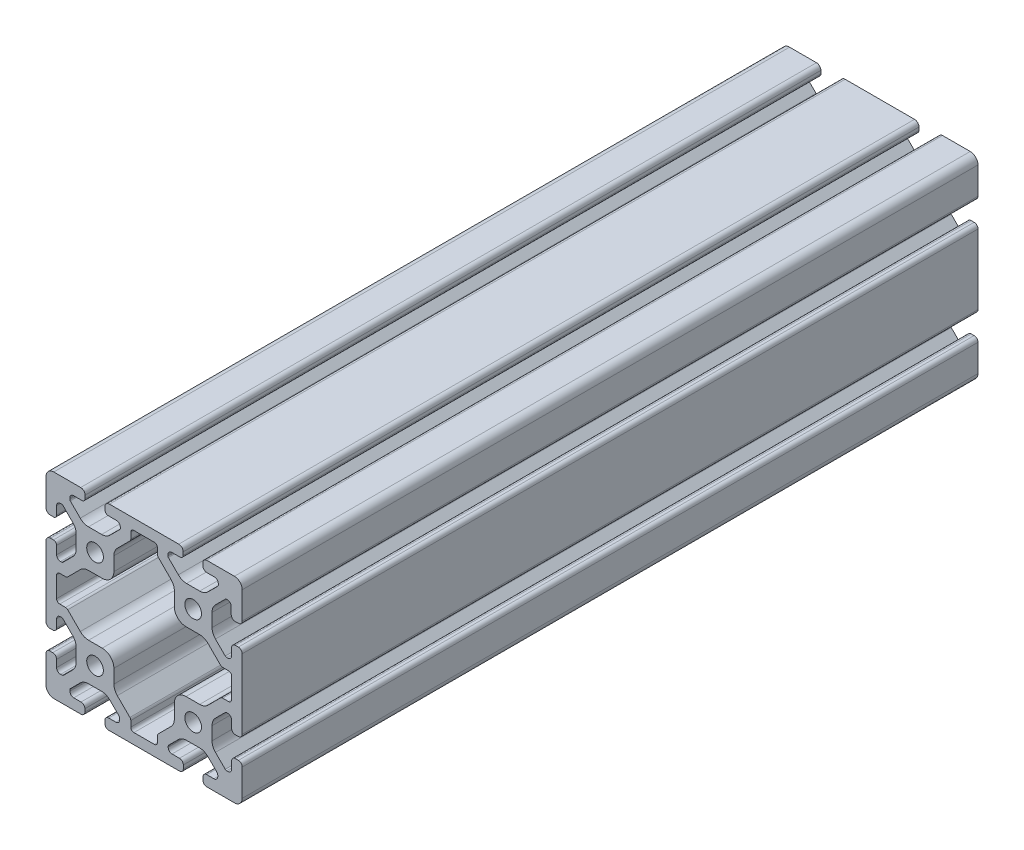
SolidWorks part; units mm, degrees
material "6105-T5 Aluminum"
ref_plane "Front Plane" through (0, 0, 0) normal (0, 0, 1) x (1, 0, 0)
ref_plane "Top Plane" through (0, 0, 0) normal (0, 1, 0) x (1, 0, 0)
ref_plane "Right Plane" through (0, 0, 0) normal (1, 0, 0) x (0, 0, -1)
sketch "Sketch1" plane through (0, 0, 0) normal (0, 0, 1) x (1, 0, 0)
  line L1 (0, 0) -> (-43.5804, 43.5804) construction
  line L2 (-20, 20) -> (-47.7323, 20) construction
  line L3 (-20, 20) -> (3.796, 43.796) construction
  line L4 (-20, 20) -> (-20, 43.5758) construction
  line L5 (-20, -27.7) -> (-20, -47.5576) construction
  line L131 (29.0912, 26.0365) -> (33.0827, 30.028)
  line L132 (27.7, 17.3222) -> (27.7, 22.6778)
  line L133 (29.0912, 13.9635) -> (33.0827, 9.972)
  line L134 (33.6201, 9.7494) -> (34.11, 9.7494)
  line L135 (35.68, 11.3194) -> (35.68, 14.2221)
  line L136 (37.25, 15.7921) -> (38.43, 15.7921)
  line L137 (40, 14.2221) -> (40, 7.0214)
  line L138 (40, 7.0214) -> (40, -7.0214)
  line L139 (40, -7.0214) -> (40, -14.2221)
  line L140 (38.43, -15.7921) -> (37.25, -15.7921)
  line L141 (35.68, -14.2221) -> (35.68, -11.3194)
  line L142 (33.6201, -9.7494) -> (34.11, -9.7494)
  line L143 (29.0912, -13.9635) -> (33.0827, -9.972)
  line L144 (27.7, -22.6778) -> (27.7, -17.3222)
  line L145 (29.0912, -26.0365) -> (33.0827, -30.028)
  line L146 (33.6201, -30.2506) -> (34.11, -30.2506)
  line L147 (35.68, -28.6806) -> (35.68, -25.7779)
  line L148 (37.25, -24.2079) -> (38.43, -24.2079)
  line L149 (40, -25.7779) -> (40, -33.0259)
  line L150 (40, -33.0259) -> (40, -36.83)
  line L151 (36.83, -40) -> (32.9998, -40)
  line L152 (32.9998, -40) -> (25.5696, -40)
  line L153 (23.9996, -38.43) -> (23.9996, -37.25)
  line L154 (25.5696, -35.68) -> (28.4723, -35.68)
  line L155 (30.0413, -34.0552) -> (30.0171, -33.3605)
  line L156 (29.7949, -32.8496) -> (26.0365, -29.0912)
  line L157 (17.3222, -27.7) -> (22.6778, -27.7)
  line L158 (10.035, -33.0197) -> (13.9635, -29.0912)
  line L159 (9.8124, -33.8926) -> (9.8124, -33.5571)
  line L160 (11.3824, -35.4626) -> (14.4246, -35.4626)
  line L161 (15.9946, -37.0326) -> (15.9946, -38.43)
  line L162 (14.4246, -40) -> (6.9987, -40)
  line L163 (6.9987, -40) -> (-6.9987, -40)
  line L164 (-6.9987, -40) -> (-14.4292, -40)
  line L165 (-15.9992, -38.43) -> (-15.9992, -37.25)
  line L166 (-14.4292, -35.68) -> (-11.5265, -35.68)
  line L167 (-9.9574, -34.0552) -> (-9.9816, -33.3618)
  line L168 (-10.2038, -32.8509) -> (-13.9635, -29.0912)
  line L169 (-22.6778, -27.7) -> (-17.3222, -27.7)
  line L170 (-30.028, -33.0827) -> (-26.0365, -29.0912)
  line L171 (-30.2506, -34.11) -> (-30.2506, -33.6201)
  line L172 (-28.6806, -35.68) -> (-25.7231, -35.68)
  line L173 (-24.1531, -37.25) -> (-24.1531, -38.43)
  line L174 (-25.7231, -40) -> (-33, -40)
  line L175 (-33, -40) -> (-36.83, -40)
  line L176 (-40, -36.83) -> (-40, -33.0191)
  line L177 (-40, -33.0191) -> (-40, -25.591)
  line L178 (-38.43, -24.021) -> (-37.25, -24.021)
  line L179 (-35.68, -28.4937) -> (-35.68, -25.591)
  line L180 (-34.0552, -30.0627) -> (-33.3827, -30.0392)
  line L181 (-32.8718, -29.8171) -> (-29.0912, -26.0365)
  line L182 (-27.7, -22.6778) -> (-27.7, -17.3222)
  line L183 (-29.0912, -13.9635) -> (-33.0827, -9.972)
  line L184 (-34.11, -9.7494) -> (-33.6201, -9.7494)
  line L185 (-35.68, -11.3194) -> (-35.68, -14.4473)
  line L186 (-38.43, -16.0173) -> (-37.25, -16.0173)
  line L187 (-40, -14.4473) -> (-40, -7.0169)
  line L188 (-40, -7.0169) -> (-40, 7.0169)
  line L189 (-40, 7.0169) -> (-40, 14.1348)
  line L190 (-38.1948, 15.94) -> (-36.9772, 15.94)
  line L191 (-35.68, 11.3194) -> (-35.68, 14.6428)
  line L192 (-34.11, 9.7494) -> (-33.6201, 9.7494)
  line L193 (-33.0827, 9.972) -> (-29.0912, 13.9635)
  line L194 (-27.7, 17.3222) -> (-27.7, 22.6778)
  line L195 (-29.0912, 26.0365) -> (-33.0827, 30.028)
  line L196 (-34.11, 30.2506) -> (-33.6201, 30.2506)
  line L197 (-35.68, 28.6806) -> (-35.68, 25.3572)
  line L198 (-38.1948, 24.06) -> (-36.9772, 24.06)
  line L199 (-40, 25.8652) -> (-40, 33.3181)
  line L200 (-40, 33.3181) -> (-40, 36.83)
  line L201 (-36.83, 40) -> (-33.0314, 40)
  line L202 (-33.0314, 40) -> (-25.8652, 40)
  line L203 (-24.06, 36.9772) -> (-24.06, 38.1948)
  line L204 (-25.3572, 35.68) -> (-28.7018, 35.68)
  line L205 (-30.285, 33.6069) -> (-30.285, 34.0968)
  line L206 (-30.0961, 33.1508) -> (-26.0365, 29.0912)
  line L207 (-22.6778, 27.7) -> (-17.3222, 27.7)
  line L208 (-13.9635, 29.0912) -> (-9.9039, 33.1508)
  line L209 (-9.715, 33.6069) -> (-9.715, 34.0968)
  line L210 (-14.6428, 35.68) -> (-11.2982, 35.68)
  line L211 (-15.94, 36.9772) -> (-15.94, 38.1948)
  line L212 (-14.1348, 40) -> (-6.9844, 40)
  line L213 (-6.9844, 40) -> (6.9844, 40)
  line L214 (6.9844, 40) -> (14.1348, 40)
  line L215 (15.94, 36.9772) -> (15.94, 38.1948)
  line L216 (14.6428, 35.68) -> (11.2982, 35.68)
  line L217 (9.715, 33.6069) -> (9.715, 34.0968)
  line L218 (9.9039, 33.1508) -> (13.9635, 29.0912)
  line L219 (17.3222, 27.7) -> (22.6778, 27.7)
  line L220 (26.0365, 29.0912) -> (30.028, 33.0827)
  line L221 (30.2506, 33.6201) -> (30.2506, 34.11)
  line L222 (25.5409, 35.679) -> (28.6258, 35.679)
  line L223 (23.9709, 37.249) -> (23.9709, 38.43)
  line L224 (25.5409, 40) -> (36.83, 40)
  line L226 (40, 36.83) -> (40, 32.9339)
  line L227 (40, 32.9339) -> (40, 25.7779)
  line L228 (38.43, 24.2079) -> (37.0956, 24.2079)
  line L229 (35.5256, 25.7779) -> (35.5256, 28.6806)
  line L230 (33.6201, 30.2506) -> (33.9556, 30.2506)
  line L231 (17.07, 12.32) -> (22.6578, 12.32)
  line L232 (26.0165, 10.9288) -> (31.1439, 5.8014)
  line L233 (32.0419, 5.4294) -> (34.41, 5.4294)
  line L234 (35.68, -4.1594) -> (35.68, 4.1594)
  line L235 (32.0419, -5.4294) -> (34.41, -5.4294)
  line L236 (26.0165, -10.9288) -> (31.1439, -5.8014)
  line L237 (17.07, -12.32) -> (22.6578, -12.32)
  line L238 (12.32, -22.6578) -> (12.32, -17.07)
  line L239 (5.8014, -31.1439) -> (10.9288, -26.0165)
  line L240 (5.4294, -34.41) -> (5.4294, -32.0419)
  line L241 (-4.1594, -35.68) -> (4.1594, -35.68)
  line L242 (-5.4294, -34.41) -> (-5.4294, -32.0419)
  line L243 (-5.8014, -31.1439) -> (-10.9288, -26.0165)
  line L244 (-12.32, -22.6578) -> (-12.32, -17.07)
  line L245 (-22.6578, -12.32) -> (-17.07, -12.32)
  line L246 (-26.0165, -10.9288) -> (-31.1439, -5.8014)
  line L247 (-34.41, -5.4294) -> (-32.0419, -5.4294)
  line L248 (-35.68, -4.1594) -> (-35.68, 4.1594)
  line L249 (-34.41, 5.4294) -> (-32.0419, 5.4294)
  line L250 (-31.1439, 5.8014) -> (-26.0165, 10.9288)
  line L251 (-22.6578, 12.32) -> (-17.07, 12.32)
  line L252 (-12.32, 17.07) -> (-12.32, 22.6578)
  line L253 (-10.9288, 26.0165) -> (-5.8014, 31.1439)
  line L254 (-5.4294, 32.0419) -> (-5.4294, 34.41)
  line L255 (-4.1594, 35.68) -> (4.1594, 35.68)
  line L256 (5.4294, 32.0419) -> (5.4294, 34.41)
  line L257 (5.8014, 31.1439) -> (10.9288, 26.0165)
  line L258 (12.32, 17.07) -> (12.32, 22.6578)
  circle A116 centre (-20, 20) radius 3.4
  circle A117 centre (20, 20) radius 3.4
  circle A118 centre (20, -20) radius 3.4
  circle A119 centre (-20, -20) radius 3.4
  arc A120 (29.0912, 26.0365) -> (27.7, 22.6778) centre (32.45, 22.6778) ccw
  arc A121 (27.7, 17.3222) -> (29.0912, 13.9635) centre (32.45, 17.3222) ccw
  arc A122 (33.0827, 9.972) -> (33.6201, 9.7494) centre (33.6201, 10.5094) ccw
  arc A123 (34.11, 9.7494) -> (35.68, 11.3194) centre (34.11, 11.3194) ccw
  arc A124 (37.25, 15.7921) -> (35.68, 14.2221) centre (37.25, 14.2221) ccw
  arc A125 (40, 14.2221) -> (38.43, 15.7921) centre (38.43, 14.2221) ccw
  arc A126 (38.43, -15.7921) -> (40, -14.2221) centre (38.43, -14.2221) ccw
  arc A127 (35.68, -14.2221) -> (37.25, -15.7921) centre (37.25, -14.2221) ccw
  arc A128 (35.68, -11.3194) -> (34.11, -9.7494) centre (34.11, -11.3194) ccw
  arc A129 (33.6201, -9.7494) -> (33.0827, -9.972) centre (33.6201, -10.5094) ccw
  arc A130 (29.0912, -13.9635) -> (27.7, -17.3222) centre (32.45, -17.3222) ccw
  arc A131 (27.7, -22.6778) -> (29.0912, -26.0365) centre (32.45, -22.6778) ccw
  arc A132 (33.0827, -30.028) -> (33.6201, -30.2506) centre (33.6201, -29.4906) ccw
  arc A133 (34.11, -30.2506) -> (35.68, -28.6806) centre (34.11, -28.6806) ccw
  arc A134 (37.25, -24.2079) -> (35.68, -25.7779) centre (37.25, -25.7779) ccw
  arc A135 (40, -25.7779) -> (38.43, -24.2079) centre (38.43, -25.7779) ccw
  arc A136 (36.83, -40) -> (40, -36.83) centre (36.83, -36.83) ccw
  arc A137 (23.9996, -38.43) -> (25.5696, -40) centre (25.5696, -38.43) ccw
  arc A138 (25.5696, -35.68) -> (23.9996, -37.25) centre (25.5696, -37.25) ccw
  arc A139 (28.4723, -35.68) -> (30.0413, -34.0552) centre (28.4723, -34.11) ccw
  arc A140 (30.0171, -33.3605) -> (29.7949, -32.8496) centre (29.2575, -33.387) ccw
  arc A141 (26.0365, -29.0912) -> (22.6778, -27.7) centre (22.6778, -32.45) ccw
  arc A142 (17.3222, -27.7) -> (13.9635, -29.0912) centre (17.3222, -32.45) ccw
  arc A143 (10.035, -33.0197) -> (9.8124, -33.5571) centre (10.5724, -33.5571) ccw
  arc A144 (9.8124, -33.8926) -> (11.3824, -35.4626) centre (11.3824, -33.8926) ccw
  arc A145 (15.9946, -37.0326) -> (14.4246, -35.4626) centre (14.4246, -37.0326) ccw
  arc A146 (14.4246, -40) -> (15.9946, -38.43) centre (14.4246, -38.43) ccw
  arc A147 (-15.9992, -38.43) -> (-14.4292, -40) centre (-14.4292, -38.43) ccw
  arc A148 (-14.4292, -35.68) -> (-15.9992, -37.25) centre (-14.4292, -37.25) ccw
  arc A149 (-11.5265, -35.68) -> (-9.9574, -34.0552) centre (-11.5265, -34.11) ccw
  arc A150 (-9.9816, -33.3618) -> (-10.2038, -32.8509) centre (-10.7412, -33.3883) ccw
  arc A151 (-13.9635, -29.0912) -> (-17.3222, -27.7) centre (-17.3222, -32.45) ccw
  arc A152 (-22.6778, -27.7) -> (-26.0365, -29.0912) centre (-22.6778, -32.45) ccw
  arc A153 (-30.028, -33.0827) -> (-30.2506, -33.6201) centre (-29.4906, -33.6201) ccw
  arc A154 (-30.2506, -34.11) -> (-28.6806, -35.68) centre (-28.6806, -34.11) ccw
  arc A155 (-24.1531, -37.25) -> (-25.7231, -35.68) centre (-25.7231, -37.25) ccw
  arc A156 (-25.7231, -40) -> (-24.1531, -38.43) centre (-25.7231, -38.43) ccw
  arc A157 (-40, -36.83) -> (-36.83, -40) centre (-36.83, -36.83) ccw
  arc A158 (-38.43, -24.021) -> (-40, -25.591) centre (-38.43, -25.591) ccw
  arc A159 (-35.68, -25.591) -> (-37.25, -24.021) centre (-37.25, -25.591) ccw
  arc A160 (-35.68, -28.4937) -> (-34.0552, -30.0627) centre (-34.11, -28.4937) ccw
  arc A161 (-33.3827, -30.0392) -> (-32.8718, -29.8171) centre (-33.4092, -29.2797) ccw
  arc A162 (-29.0912, -26.0365) -> (-27.7, -22.6778) centre (-32.45, -22.6778) ccw
  arc A163 (-27.7, -17.3222) -> (-29.0912, -13.9635) centre (-32.45, -17.3222) ccw
  arc A164 (-33.0827, -9.972) -> (-33.6201, -9.7494) centre (-33.6201, -10.5094) ccw
  arc A165 (-34.11, -9.7494) -> (-35.68, -11.3194) centre (-34.11, -11.3194) ccw
  arc A166 (-37.25, -16.0173) -> (-35.68, -14.4473) centre (-37.25, -14.4473) ccw
  arc A167 (-40, -14.4473) -> (-38.43, -16.0173) centre (-38.43, -14.4473) ccw
  arc A168 (-38.1948, 15.94) -> (-40, 14.1348) centre (-38.1948, 14.1348) ccw
  arc A169 (-35.68, 14.6428) -> (-36.9772, 15.94) centre (-36.9772, 14.6428) ccw
  arc A170 (-35.68, 11.3194) -> (-34.11, 9.7494) centre (-34.11, 11.3194) ccw
  arc A171 (-33.6201, 9.7494) -> (-33.0827, 9.972) centre (-33.6201, 10.5094) ccw
  arc A172 (-29.0912, 13.9635) -> (-27.7, 17.3222) centre (-32.45, 17.3222) ccw
  arc A173 (-27.7, 22.6778) -> (-29.0912, 26.0365) centre (-32.45, 22.6778) ccw
  arc A174 (-33.0827, 30.028) -> (-33.6201, 30.2506) centre (-33.6201, 29.4906) ccw
  arc A175 (-34.11, 30.2506) -> (-35.68, 28.6806) centre (-34.11, 28.6806) ccw
  arc A176 (-36.9772, 24.06) -> (-35.68, 25.3572) centre (-36.9772, 25.3572) ccw
  arc A177 (-40, 25.8652) -> (-38.1948, 24.06) centre (-38.1948, 25.8652) ccw
  arc A178 (-36.83, 40) -> (-40, 36.83) centre (-36.83, 36.83) ccw
  arc A179 (-24.06, 38.1948) -> (-25.8652, 40) centre (-25.8652, 38.1948) ccw
  arc A180 (-25.3572, 35.68) -> (-24.06, 36.9772) centre (-25.3572, 36.9772) ccw
  arc A181 (-28.7018, 35.68) -> (-30.285, 34.0968) centre (-28.7018, 34.0968) ccw
  arc A182 (-30.285, 33.6069) -> (-30.0961, 33.1508) centre (-29.6399, 33.6069) ccw
  arc A183 (-26.0365, 29.0912) -> (-22.6778, 27.7) centre (-22.6778, 32.45) ccw
  arc A184 (-17.3222, 27.7) -> (-13.9635, 29.0912) centre (-17.3222, 32.45) ccw
  arc A185 (-9.9039, 33.1508) -> (-9.715, 33.6069) centre (-10.3601, 33.6069) ccw
  arc A186 (-9.715, 34.0968) -> (-11.2982, 35.68) centre (-11.2982, 34.0968) ccw
  arc A187 (-15.94, 36.9772) -> (-14.6428, 35.68) centre (-14.6428, 36.9772) ccw
  arc A188 (-14.1348, 40) -> (-15.94, 38.1948) centre (-14.1348, 38.1948) ccw
  arc A189 (15.94, 38.1948) -> (14.1348, 40) centre (14.1348, 38.1948) ccw
  arc A190 (14.6428, 35.68) -> (15.94, 36.9772) centre (14.6428, 36.9772) ccw
  arc A191 (11.2982, 35.68) -> (9.715, 34.0968) centre (11.2982, 34.0968) ccw
  arc A192 (9.715, 33.6069) -> (9.9039, 33.1508) centre (10.3601, 33.6069) ccw
  arc A193 (13.9635, 29.0912) -> (17.3222, 27.7) centre (17.3222, 32.45) ccw
  arc A194 (22.6778, 27.7) -> (26.0365, 29.0912) centre (22.6778, 32.45) ccw
  arc A195 (30.028, 33.0827) -> (30.2506, 33.6201) centre (29.4906, 33.6201) ccw
  arc A196 (30.2506, 34.11) -> (28.6258, 35.679) centre (28.6806, 34.11) ccw
  arc A197 (23.9709, 37.249) -> (25.5409, 35.679) centre (25.5409, 37.249) ccw
  arc A198 (25.5409, 40) -> (23.9709, 38.43) centre (25.5409, 38.43) ccw
  arc A199 (40, 36.83) -> (36.83, 40) centre (36.83, 36.83) ccw
  arc A200 (38.43, 24.2079) -> (40, 25.7779) centre (38.43, 25.7779) ccw
  arc A201 (35.5256, 25.7779) -> (37.0956, 24.2079) centre (37.0956, 25.7779) ccw
  arc A202 (35.5256, 28.6806) -> (33.9556, 30.2506) centre (33.9556, 28.6806) ccw
  arc A203 (33.6201, 30.2506) -> (33.0827, 30.028) centre (33.6201, 29.4906) ccw
  arc A204 (26.0165, 10.9288) -> (22.6578, 12.32) centre (22.6578, 7.57) ccw
  arc A205 (31.1439, 5.8014) -> (32.0419, 5.4294) centre (32.0419, 6.6994) ccw
  arc A206 (35.68, 4.1594) -> (34.41, 5.4294) centre (34.41, 4.1594) ccw
  arc A207 (34.41, -5.4294) -> (35.68, -4.1594) centre (34.41, -4.1594) ccw
  arc A208 (32.0419, -5.4294) -> (31.1439, -5.8014) centre (32.0419, -6.6994) ccw
  arc A209 (22.6578, -12.32) -> (26.0165, -10.9288) centre (22.6578, -7.57) ccw
  arc A210 (17.07, -12.32) -> (12.32, -17.07) centre (17.07, -17.07) ccw
  arc A211 (10.9288, -26.0165) -> (12.32, -22.6578) centre (7.57, -22.6578) ccw
  arc A212 (5.8014, -31.1439) -> (5.4294, -32.0419) centre (6.6994, -32.0419) ccw
  arc A213 (4.1594, -35.68) -> (5.4294, -34.41) centre (4.1594, -34.41) ccw
  arc A214 (-5.4294, -34.41) -> (-4.1594, -35.68) centre (-4.1594, -34.41) ccw
  arc A215 (-5.4294, -32.0419) -> (-5.8014, -31.1439) centre (-6.6994, -32.0419) ccw
  arc A216 (-12.32, -22.6578) -> (-10.9288, -26.0165) centre (-7.57, -22.6578) ccw
  arc A217 (-12.32, -17.07) -> (-17.07, -12.32) centre (-17.07, -17.07) ccw
  arc A218 (-26.0165, -10.9288) -> (-22.6578, -12.32) centre (-22.6578, -7.57) ccw
  arc A219 (-31.1439, -5.8014) -> (-32.0419, -5.4294) centre (-32.0419, -6.6994) ccw
  arc A220 (-35.68, -4.1594) -> (-34.41, -5.4294) centre (-34.41, -4.1594) ccw
  arc A221 (-34.41, 5.4294) -> (-35.68, 4.1594) centre (-34.41, 4.1594) ccw
  arc A222 (-32.0419, 5.4294) -> (-31.1439, 5.8014) centre (-32.0419, 6.6994) ccw
  arc A223 (-22.6578, 12.32) -> (-26.0165, 10.9288) centre (-22.6578, 7.57) ccw
  arc A224 (-17.07, 12.32) -> (-12.32, 17.07) centre (-17.07, 17.07) ccw
  arc A225 (-10.9288, 26.0165) -> (-12.32, 22.6578) centre (-7.57, 22.6578) ccw
  arc A226 (-5.8014, 31.1439) -> (-5.4294, 32.0419) centre (-6.6994, 32.0419) ccw
  arc A227 (-4.1594, 35.68) -> (-5.4294, 34.41) centre (-4.1594, 34.41) ccw
  arc A228 (5.4294, 34.41) -> (4.1594, 35.68) centre (4.1594, 34.41) ccw
  arc A229 (5.4294, 32.0419) -> (5.8014, 31.1439) centre (6.6994, 32.0419) ccw
  arc A230 (12.32, 22.6578) -> (10.9288, 26.0165) centre (7.57, 22.6578) ccw
  arc A231 (12.32, 17.07) -> (17.07, 12.32) centre (17.07, 17.07) ccw
  dimension "D8" = 6.8
  dimension "D1" = 80
  dimension "D2" = 40
  dimension "D3" = 20
  dimension "D4" = 20.57
  dimension "D5" = 4.32
  dimension "D6" = 4.32
  dimension "D7" = 8.12
  dimension "D9" = 4.32
  dimension "D10" = 12.3
extrude "Extrude1" add sketch "Sketch1" against normal blind 300
